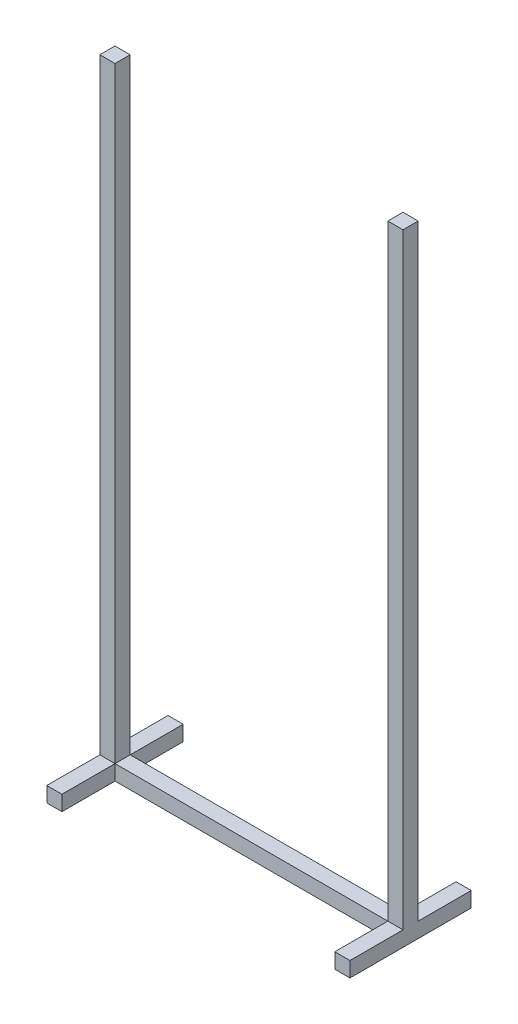
SolidWorks part; units mm, degrees
ref_plane "前视基准面" through (0, 0, 0) normal (0, 0, 1) x (1, 0, 0)
ref_plane "上视基准面" through (0, 0, 0) normal (0, 1, 0) x (1, 0, 0)
ref_plane "右视基准面" through (0, 0, 0) normal (1, 0, 0) x (0, 0, -1)
other "Configuration Table"
sketch "草图1" plane through (0, 0, 0) normal (0, 1, 0) x (1, 0, 0)
  line L1 (-100, -5) -> (100, -5)
  line L2 (-100, -5) -> (-100, 5)
  line L3 (-100, 5) -> (100, 5)
  line L4 (100, -5) -> (100, 5)
  line L5 (-100, -5) -> (100, 5) construction
  line L6 (-100, 5) -> (100, -5) construction
  line L7 (-90, -40) -> (-100, -40)
  line L8 (-90, -40) -> (-90, 40)
  line L9 (-90, 40) -> (-100, 40)
  line L10 (-100, -40) -> (-100, 40)
  line L11 (-90, -40) -> (-100, 40) construction
  line L12 (-90, 40) -> (-100, -40) construction
  line L13 (90, -40) -> (100, -40)
  line L14 (90, -40) -> (90, 40)
  line L15 (90, 40) -> (100, 40)
  line L16 (100, -40) -> (100, 40)
  line L17 (90, -40) -> (100, 40) construction
  line L18 (90, 40) -> (100, -40) construction
  point P0 (0, 0)
  point P5 (-95, 0)
  point P11 (95, 0)
  point P17 (100, 0)
  dimension "D1" = 10
  dimension "D2" = 200
  dimension "D3" = 10
  dimension "D4" = 10
  dimension "D5" = 80
  dimension "D6" = 80
extrude "凸台-拉伸1" add sketch "草图1" along normal blind 10 contours L1 L8 L3 L2 | L1 L14 L3 L8 | L10 L7 L8 L1 | L10 L3 L8 L9 | L3 L16 L15 L14 | L14 L1 L4 L3 | L13 L16 L1 L14
sketch "草图2" plane through (0, 10, 0) normal (0, 1, 0) x (1, 0, 0)
  line L0 (100, -40) -> (100, 40) construction
  line L1 (-100, -5) -> (-90, -5)
  line L2 (-100, -5) -> (-100, 5)
  line L3 (-100, 5) -> (-90, 5)
  line L4 (-90, -5) -> (-90, 5)
  line L5 (-100, -5) -> (-90, 5) construction
  line L6 (-100, 5) -> (-90, -5) construction
  line L7 (100, -5) -> (90, -5)
  line L8 (100, -5) -> (100, 5)
  line L9 (100, 5) -> (90, 5)
  line L10 (90, -5) -> (90, 5)
  line L11 (100, -5) -> (90, 5) construction
  line L12 (100, 5) -> (90, -5) construction
  line L13 (-100, -40) -> (-100, 40) construction
  point P0 (-95, 0)
  point P5 (95, 0)
extrude "凸台-拉伸2" add sketch "草图2" along normal blind 400
